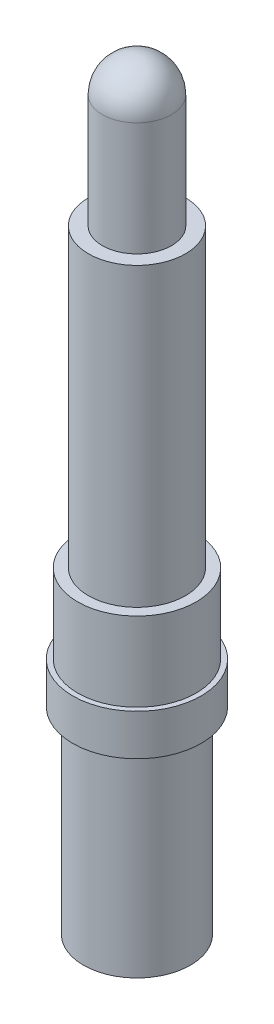
SolidWorks part; units mm, degrees
ref_plane "Front Plane" through (0, 0, 0) normal (0, 0, 1) x (1, 0, 0)
ref_plane "Top Plane" through (0, 0, 0) normal (0, 1, 0) x (1, 0, 0)
ref_plane "Right Plane" through (0, 0, 0) normal (1, 0, 0) x (0, 0, -1)
sketch "Sketch2" plane through (0, 0, 0) normal (0, 0, 1) x (1, 0, 0)
  line L0 (0, 0) -> (0, 11.2268) construction
  line L1 (0.5334, 11.2268) -> (0.5334, 9.4742)
  line L2 (0.5334, 9.4742) -> (0.7493, 9.4742)
  line L3 (0.7493, 9.4742) -> (0.7493, 4.9022)
  line L4 (0.7493, 4.9022) -> (0.9144, 4.9022)
  line L5 (0.9144, 4.9022) -> (0.9144, 3.683)
  line L6 (0.9144, 3.683) -> (0.9906, 3.683)
  line L7 (0.9906, 3.683) -> (0.9906, 3.048)
  line L8 (0.9906, 3.048) -> (0.8255, 3.048)
  line L9 (0.8255, 3.048) -> (0.8255, 0)
  line L10 (0.8255, 0) -> (0, 0)
  line L11 (0, 0) -> (0, 11.7602)
  line L12 (0, 0) -> (0, -5.7752) construction
  arc A0 (0, 11.7602) -> (0.5334, 11.2268) centre (0, 11.2268) cw
  point P14 (0.8255, -4.7986)
  point P18 (0.9906, -1.9789)
  point P19 (0.7493, 3.1946)
  point P20 (0.9144, 0.1359)
  point P21 (0.9144, -1.9072)
  point P22 (0.5334, 5.3858)
  point P23 (0.9144, 4.5084)
  point P24 (0, -0.137)
  dimension "D1" = 1.0668
  dimension "D2" = 1.9812
  dimension "D3" = 1.8288
  dimension "D4" = 1.4986
  dimension "D5" = 2.286
  dimension "D6" = 1.651
  dimension "D7" = 6.4262
  dimension "D8" = 0.635
  dimension "D9" = 4.572
  dimension "D10" = 3.048
revolve "Revolve1" add sketch "Sketch2" angle 360 about L12
ref_point "Point1"
